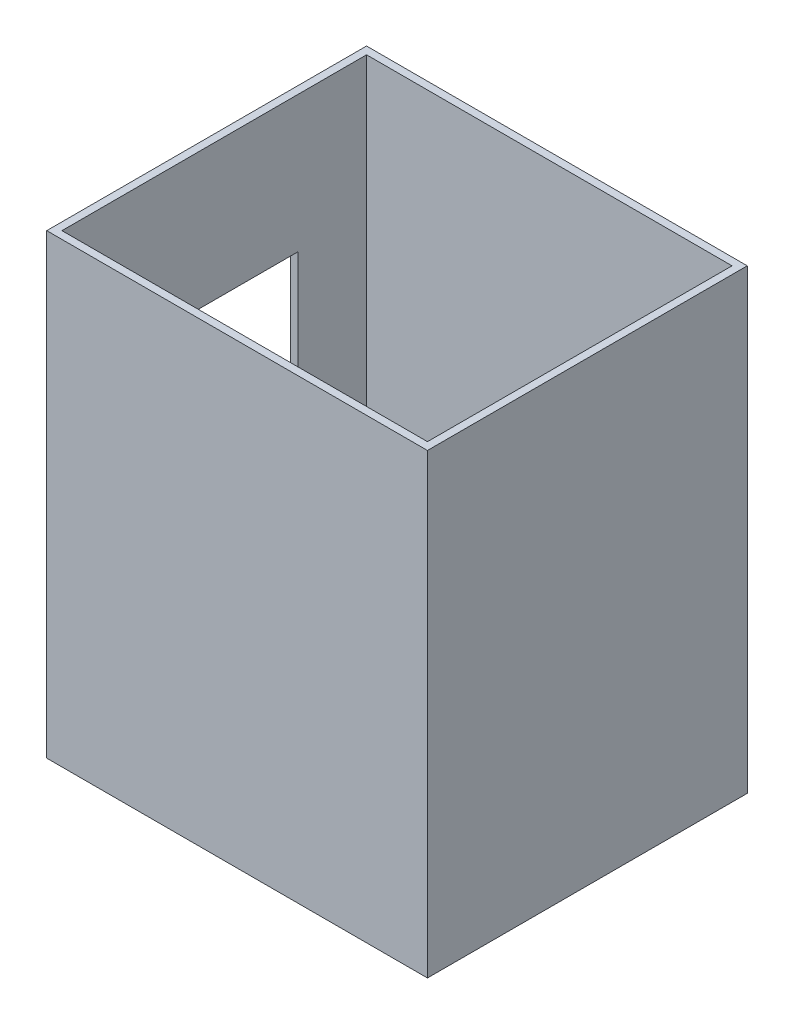
SolidWorks part; units mm, degrees
ref_plane "Front Plane" through (0, 0, 0) normal (0, 0, 1) x (1, 0, 0)
ref_plane "Top Plane" through (0, 0, 0) normal (0, 1, 0) x (1, 0, 0)
ref_plane "Right Plane" through (0, 0, 0) normal (1, 0, 0) x (0, 0, -1)
sketch "Sketch1" plane through (0, 0, 0) normal (0, 1, 0) x (1, 0, 0)
  line L1 (1250, -1050) -> (-1250, -1050)
  line L2 (1250, -1050) -> (1250, 1050)
  line L3 (1250, 1050) -> (-1250, 1050)
  line L4 (-1250, -1050) -> (-1250, 1050)
  line L5 (1250, -1050) -> (-1250, 1050) construction
  line L6 (1250, 1050) -> (-1250, -1050) construction
  point P0 (0, 0)
  dimension "D1" = 2100
  dimension "D2" = 2500
extrude "Boss-Extrude1" add sketch "Sketch1" along normal blind 3000
shell "Shell1" thickness 50
sketch "Sketch2" plane through (-1250, 0, 0) normal (-1, 0, 0) x (0, 0, 1)
  line L0 (0, 0) -> (0, 2974.6168) construction
  line L1 (-550, 2105) -> (550, 2105)
  line L2 (-550, 2105) -> (-550, 5)
  line L3 (-550, 5) -> (550, 5)
  line L4 (550, 2105) -> (550, 5)
  line L5 (-550, 2105) -> (550, 5) construction
  line L6 (-550, 5) -> (550, 2105) construction
  line L7 (-1050, 0) -> (1050, 0) construction
  point P4 (0, 1055)
  point P9 (0, 0)
  dimension "D1" = 2105
  dimension "D2" = 2100
  dimension "D3" = 1100
extrude "Cut-Extrude1" cut sketch "Sketch2" against normal blind 50
